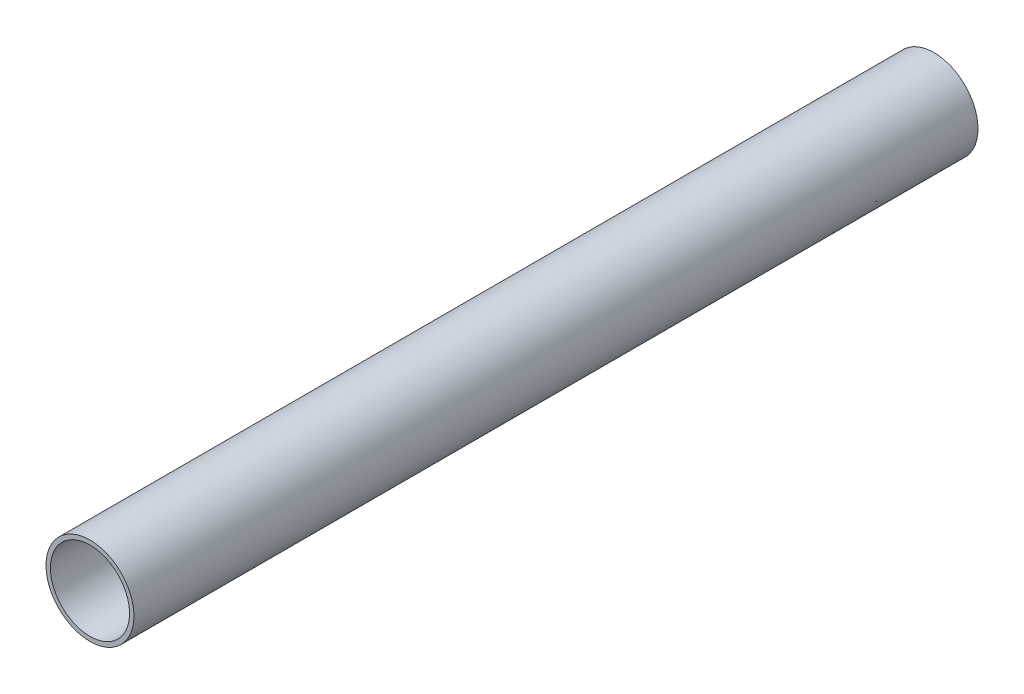
SolidWorks part; units mm, degrees
material "Galvanized Steel"
ref_plane "Front Plane" through (0, 0, 0) normal (0, 0, 1) x (1, 0, 0)
ref_plane "Top Plane" through (0, 0, 0) normal (0, 1, 0) x (1, 0, 0)
ref_plane "Right Plane" through (0, 0, 0) normal (1, 0, 0) x (0, 0, -1)
sketch "Sketch1" plane through (0, 0, 0) normal (0, 0, 1) x (1, 0, 0)
  circle A0 centre (0, 0) radius 15.875
  circle A1 centre (0, 0) radius 14.2875
  dimension "D1" = 1.5875
  dimension "D2" = 31.75
extrude "Boss-Extrude1" add sketch "Sketch1" along normal blind 914.4
sketch "Sketch2" plane through (0, 0, 0) normal (1, 0, 0) x (0, 0, -1)
  line L0 (-914.4, -15.875) -> (0, -15.875) construction
  line L1 (-914.4, 15.875) -> (-304.8, 15.875)
  line L2 (-914.4, 15.875) -> (-914.4, -15.875)
  line L3 (-914.4, -15.875) -> (-304.8, -15.875)
  line L4 (-304.8, 15.875) -> (-304.8, -15.875)
  dimension "D1" = 304.8
extrude "Cut-Extrude1" cut sketch "Sketch2" against normal through all and the other way through all
